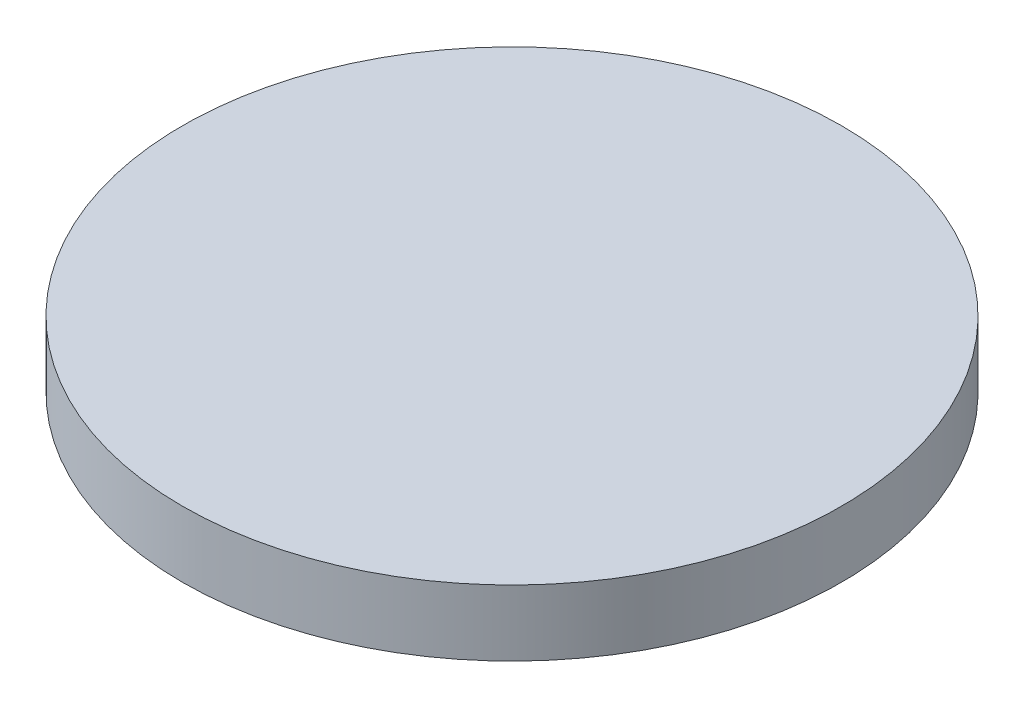
SolidWorks part; units mm, degrees
ref_plane "Front Plane" through (0, 0, 0) normal (0, 0, 1) x (1, 0, 0)
ref_plane "Top Plane" through (0, 0, 0) normal (0, 1, 0) x (1, 0, 0)
ref_plane "Right Plane" through (0, 0, 0) normal (1, 0, 0) x (0, 0, -1)
sketch "Sketch1" plane through (0, 0, 0) normal (0, 1, 0) x (1, 0, 0)
  circle A0 centre (0, 0) radius 50
  dimension "D1" = 100
extrude "Boss-Extrude1" add sketch "Sketch1" along normal blind 10
sketch "Sketch2" plane through (0, 10, 0) normal (0, 1, 0) x (1, 0, 0)
  line L0 (0, 0) -> (0, 30)
  circle A0 centre (0, 30) radius 9.5
  dimension "D2" = 19
  dimension "D1" = 30
